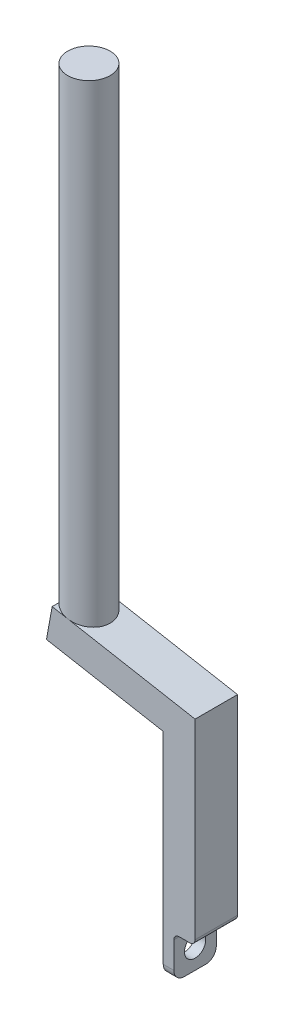
SolidWorks part; units mm, degrees
material "1.0037 (S235JR)"
ref_plane "Płaszczyzna przednia" through (0, 0, 0) normal (0, 0, 1) x (1, 0, 0)
ref_plane "Płaszczyzna górna" through (0, 0, 0) normal (0, 1, 0) x (1, 0, 0)
ref_plane "Płaszczyzna prawa" through (0, 0, 0) normal (1, 0, 0) x (0, 0, -1)
sketch "Szkic1" plane through (0, 0, 0) normal (0, 1, 0) x (1, 0, 0)
  circle A0 centre (0, 0) radius 20
  dimension "D1" = 40
extrude "Dodanie-wyciągnięcie1" add sketch "Szkic1" along normal blind 470
sketch "Szkic2" plane through (0, 0, 0) normal (0, 0, 1) x (1, 0, 0)
  line L0 (-20, 0) -> (90, -20)
  line L1 (90, -20) -> (90, -220)
  line L2 (-20, 0) -> (20, 0) construction
  line L3 (-14.6334, 29.5161) -> (120, 5.0373)
  line L4 (120, 5.0373) -> (120, -220)
  line L5 (90, -220) -> (120, -220)
  line L6 (-20, 0) -> (-14.6334, 29.5161)
  dimension "D1" = 110
  dimension "D2" = 20
  dimension "D3" = 200
  dimension "D4" = 30
extrude "Dodanie-wyciągnięcie2" add sketch "Szkic2" along normal blind 20 and the other way blind 20
sketch "Szkic3" plane through (90, 0, 0) normal (-1, 0, 0) x (0, 0, 1)
  line L0 (-20, -220) -> (20, -220) construction
  circle A0 centre (0, -200) radius 10
  dimension "D1" = 20
  dimension "D2" = 20
extrude "Wytnij-wyciągnięcie1" cut sketch "Szkic3" against normal up to next
sketch "Szkic4" plane through (120, 0, 0) normal (1, 0, 0) x (0, 0, -1)
  line L0 (20, -220) -> (-20, -220) construction
  line L1 (20, -220) -> (-20, -220)
  line L2 (-20, -220) -> (-20, -180)
  line L3 (-20, -220) -> (-20, 5.0373) construction
  line L4 (-20, -180) -> (20, -180)
  line L5 (20, -220) -> (20, 5.0373) construction
  line L6 (20, -180) -> (20, -220)
  dimension "D1" = 40
extrude "Wytnij-wyciągnięcie2" cut sketch "Szkic4" against normal blind 20
fillet "Zaokrąglenie1" radius 5 2 edges at (120, -180, 0) (100, -180, 0)
fillet "Zaokrąglenie2" radius 10 2 edges at (95, -220, -20) (95, -220, 20)
